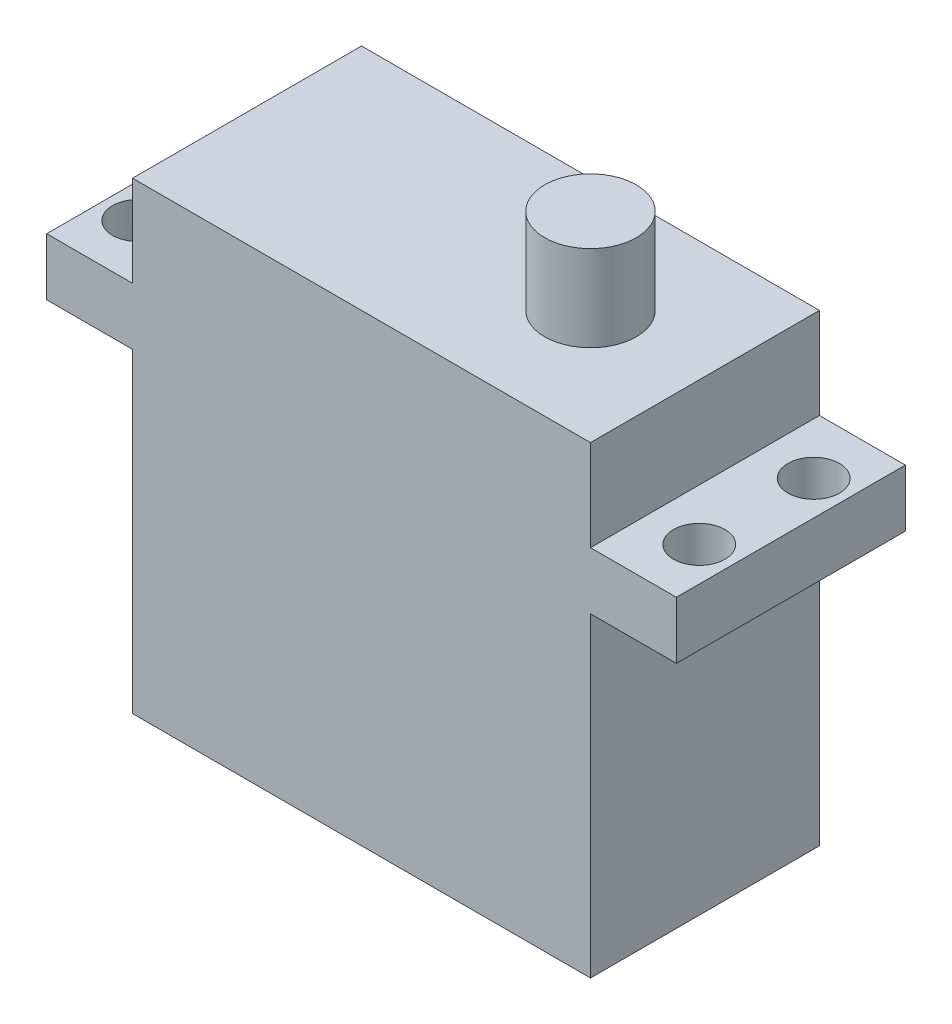
SolidWorks part; units mm, degrees
ref_plane "Front Plane" through (0, 0, 0) normal (0, 0, 1) x (1, 0, 0)
ref_plane "Top Plane" through (0, 0, 0) normal (0, 1, 0) x (1, 0, 0)
ref_plane "Right Plane" through (0, 0, 0) normal (1, 0, 0) x (0, 0, -1)
sketch "Sketch1" plane through (0, 0, 0) normal (0, 1, 0) x (1, 0, 0)
  line L1 (-20, 10) -> (20, 10)
  line L2 (-20, 10) -> (-20, -10)
  line L3 (-20, -10) -> (20, -10)
  line L4 (20, 10) -> (20, -10)
  line L5 (0, -10) -> (0, 10) construction
  line L6 (-20, 0) -> (20, 0) construction
  point P0 (0, 0)
  dimension "D1" = 20
  dimension "D2" = 40
extrude "Boss-Extrude1" add sketch "Sketch1" along normal blind 40.5
sketch "Sketch2" plane through (20, 0, 0) normal (1, 0, 0) x (0, 0, -1)
  line L0 (-10, 40.5) -> (-10, 0) construction
  line L1 (-10, 32.55) -> (10, 32.55)
  line L2 (-10, 32.55) -> (-10, 27.55)
  line L3 (-10, 27.55) -> (10, 27.55)
  line L4 (10, 32.55) -> (10, 27.55)
  line L5 (-10, 32.55) -> (10, 27.55) construction
  line L6 (-10, 27.55) -> (10, 32.55) construction
  line L7 (10, 40.5) -> (10, 0) construction
  line L8 (-10, 40.5) -> (10, 40.5) construction
  point P4 (0, 30.05)
  dimension "D1" = 12.95
  dimension "D2" = 5
extrude "Boss-Extrude2" add sketch "Sketch2" along normal blind 7.5
mirror "Mirror1" about plane through (0, 0, 0) normal (1, 0, 0) of "Boss-Extrude2"
sketch "Sketch3" plane through (0, 0, 0) normal (0, 1, 0) x (1, 0, 0)
  line L0 (27.5, 0) -> (-27.5, 0) construction
  line L1 (-27.5, 10) -> (-27.5, -10) construction
  line L2 (0, -11) -> (0, 11) construction
  circle A0 centre (-24.5, 5) radius 2.25
  circle A1 centre (24.5, 5) radius 2.25
  circle A2 centre (24.5, -5) radius 2.25
  circle A3 centre (-24.5, -5) radius 2.25
  point P6 (0, 0)
  dimension "D2" = 4.5
  dimension "D3" = 5
  dimension "D1" = 24.5
extrude "Cut-Extrude1" cut sketch "Sketch3" along normal through all
sketch "Sketch4" plane through (0, 40.5, 0) normal (0, 1, 0) x (1, 0, 0)
  circle A0 centre (10, 0) radius 4
  circle A1 centre (24.5, 5) radius 2.25 construction
  point P4 (0, 0)
  dimension "D1" = 8
  dimension "D2" = 14.5
extrude "Boss-Extrude3" add sketch "Sketch4" along normal blind 7.5
